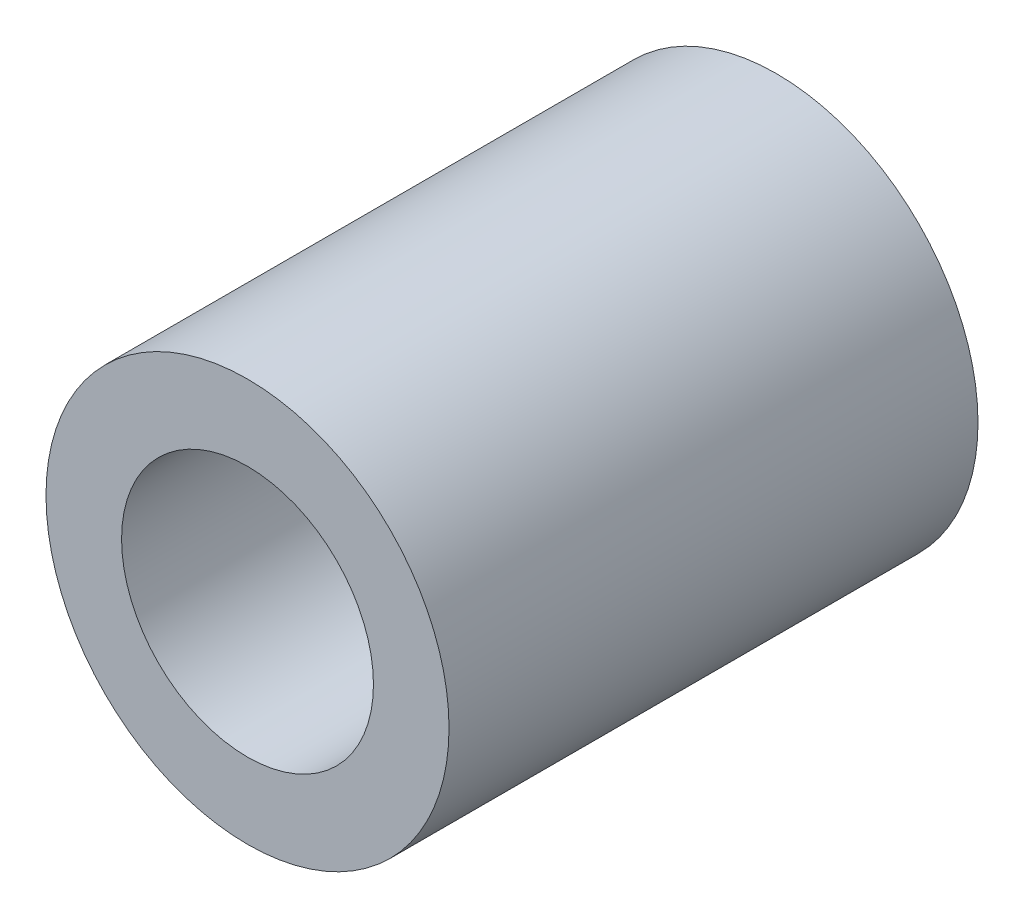
SolidWorks part; units mm, degrees
ref_plane "前视基准面" through (0, 0, 0) normal (0, 0, 1) x (1, 0, 0)
ref_plane "上视基准面" through (0, 0, 0) normal (0, 1, 0) x (1, 0, 0)
ref_plane "右视基准面" through (0, 0, 0) normal (1, 0, 0) x (0, 0, -1)
sketch "草图1" plane through (0, 0, 0) normal (0, 0, 1) x (1, 0, 0)
  circle A0 centre (0, 0) radius 10
  circle A1 centre (0, 0) radius 16
  dimension "D1" = 20
  dimension "D2" = 32
extrude "凸台-拉伸1" add sketch "草图1" along normal mid plane 42
